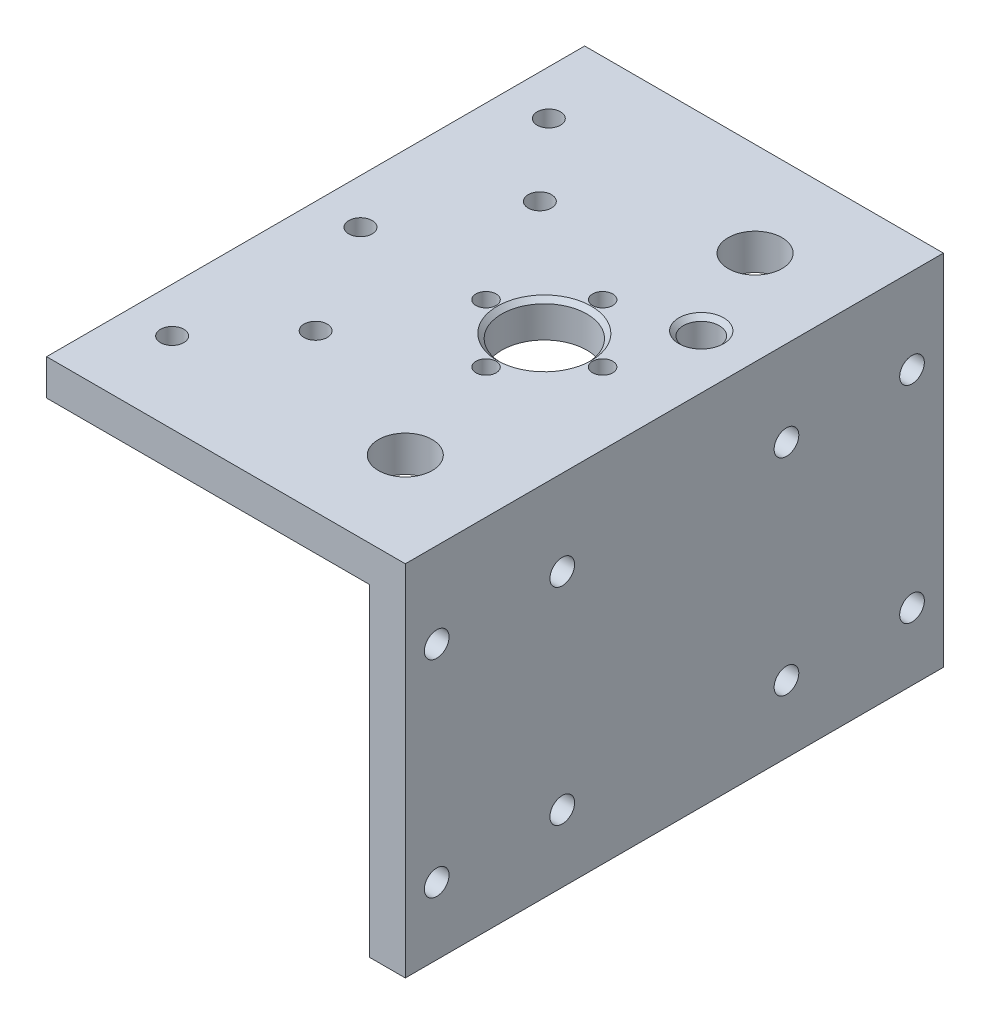
SolidWorks part; units mm, degrees
material "Lega 1060"
ref_plane "Piano frontale" through (0, 0, 0) normal (0, 0, 1) x (1, 0, 0)
ref_plane "Piano superiore" through (0, 0, 0) normal (0, 1, 0) x (1, 0, 0)
ref_plane "Piano destro" through (0, 0, 0) normal (1, 0, 0) x (0, 0, -1)
sketch "Schizzo1" plane through (0, 0, 0) normal (0, 0, 1) x (1, 0, 0)
  line L0 (0, 0) -> (-80, 0)
  line L1 (-80, 0) -> (-80, -8)
  line L2 (-80, -8) -> (-8, -8)
  line L3 (-8, -8) -> (-8, -80)
  line L4 (-8, -80) -> (0, -80)
  line L5 (0, -80) -> (0, 0)
  dimension "D1" = 80
  dimension "D2" = 80
  dimension "D3" = 8
  dimension "D4" = 8
extrude "Estrusione-Estrusione1" add sketch "Schizzo1" along normal blind 120
sketch "Schizzo12" plane through (0, 0, 0) normal (1, 0, 0) x (0, 0, -1)
  line L0 (0, -8) -> (-120, -8) construction
  line L1 (-21, 0) -> (-21, 18.8536) construction
  line L5 (0, -80) -> (0, 0) construction
  line L6 (-120, -80) -> (-120, 0) construction
  line L7 (-120, 0) -> (0, 0) construction
  line L8 (-113, -19) -> (10.4492, -19) construction
  line L9 (-113, -65) -> (16.1501, -65) construction
  line L10 (-99, -47.4454) -> (-99, 40.839) construction
  circle A0 centre (-113, -19) radius 2.75
  circle A1 centre (-85, -19) radius 2.75
  circle A6 centre (-35, -19) radius 2.75
  circle A7 centre (-7, -19) radius 2.75
  circle A10 centre (-85, -65) radius 2.75
  circle A11 centre (-113, -65) radius 2.75
  circle A12 centre (-7, -65) radius 2.75
  circle A13 centre (-35, -65) radius 2.75
  dimension "D1" = 5.5
  dimension "D5" = 28
  dimension "D6" = 28
  dimension "D7" = 28
  dimension "D8" = 28
  dimension "D2" = 8
  dimension "D3" = 11
  dimension "D4" = 57
  dimension "D9" = 21
  dimension "D10" = 21
sketch "Schizzo6" plane through (0, 0, 0) normal (0, 1, 0) x (1, 0, 0)
  line L0 (-21, -0.5808) -> (-21, -110.5835) construction
  line L2 (0, 0) -> (-80, 0) construction
  line L3 (-32.5218, -60) -> (-8.0464, -60) construction
  line L6 (0, -120) -> (-80, -120) construction
  circle A0 centre (-21, -21) radius 6
  circle A1 centre (-21, -99) radius 6
  dimension "D2" = 12
  dimension "D1" = 13
  dimension "D3" = 21
extrude "Taglio-Estrusione2" cut sketch "Schizzo6" against normal up to next
sketch "Schizzo7" plane through (0, 0, 0) normal (0, 1, 0) x (1, 0, 0)
  line L0 (-53.636, -60) -> (3.6289, -60) construction
  line L1 (0, -120) -> (-80, -120) construction
  line L2 (0, 0) -> (-80, 0) construction
  line L3 (-21, -21) -> (-21, -99) construction
  line L4 (0, -120) -> (0, 0) construction
  circle A0 centre (-29, -60) radius 9.5
  circle A1 centre (-12, -42) radius 4
  dimension "D1" = 19
  dimension "D2" = 8
  dimension "D3" = 8
  dimension "D4" = 12
  dimension "D5" = 42
extrude "Taglio-Estrusione3" cut sketch "Schizzo7" against normal up to next
hole_wizard "Foro per Vite M4-2" positions "Schizzo9" profile "Schizzo8" hole size "M4" standard "ISO" end condition through all
sketch "Schizzo9" plane through (0, 0, 0) normal (0, 1, 0) x (1, 0, 0)
  line L0 (-18.4657, -60) -> (-16, -60) construction
  line L2 (-29, -57.7684) -> (-29, -66.5063) construction
  circle A2 centre (-29, -60) radius 9.5 construction
  point P0 (-29, -47)
  point P2 (-42, -60)
  point P4 (-29, -73)
  point P8 (-16, -60)
  point P20 (-29, -60)
  dimension "D1" = 26
  dimension "D2" = 13
  dimension "D3" = 13
sketch "Schizzo8" plane through (-29, 0, 47) normal (1, 0, 0) x (0, 0, 1)
  line L0 (0, 0) -> (0, 80)
  line L1 (0, 80) -> (2.25, 80)
  line L2 (2.25, 80) -> (2.25, 0)
  line L5 (2.25, 0) -> (0, 0)
  line L11 (0, -6.35) -> (0, 107.95) construction
  dimension "Thru Hole Dia." = 4.5
  dimension "Thru Hole Depth" = 80
extrude "Taglio-Estrusione4" cut sketch "Schizzo12" against normal blind 10
sketch "Schizzo14" plane through (0, 0, 0) normal (0, 1, 0) x (1, 0, 0)
  line L0 (-70, 0) -> (-70, -120) construction
  line L1 (0, 0) -> (-80, 0) construction
  line L2 (0, -120) -> (-80, -120) construction
  line L3 (-80, -120) -> (-80, 0) construction
  line L4 (-55, 0) -> (-55, -120) construction
  line L5 (-21, -99) -> (-80, -99) construction
  line L6 (-80, -60) -> (0, -60) construction
  line L7 (0, -120) -> (0, 0) construction
  line L8 (-21, -21) -> (-80, -21) construction
  circle A0 centre (-70, -18) radius 2.6
  circle A1 centre (-70, -60) radius 2.6
  circle A2 centre (-70, -102) radius 2.6
  circle A3 centre (-55, -35) radius 2.6
  circle A4 centre (-55, -85) radius 2.6
  dimension "D3" = 5.2
  dimension "D4" = 5.2
  dimension "D5" = 5.2
  dimension "D6" = 5.2
  dimension "D7" = 5.2
  dimension "D1" = 10
  dimension "D2" = 25
  dimension "D8" = 35
  dimension "D9" = 35
  dimension "D10" = 25
  dimension "D11" = 42
extrude "Taglio-Estrusione5" cut sketch "Schizzo14" against normal blind 10
chamfer "Smusso1" distance 1 angle 45 1 edges at (-16, 0, 42)
chamfer "Smusso2" distance 1 angle 45 1 edges at (-38.5, 0, 60)
